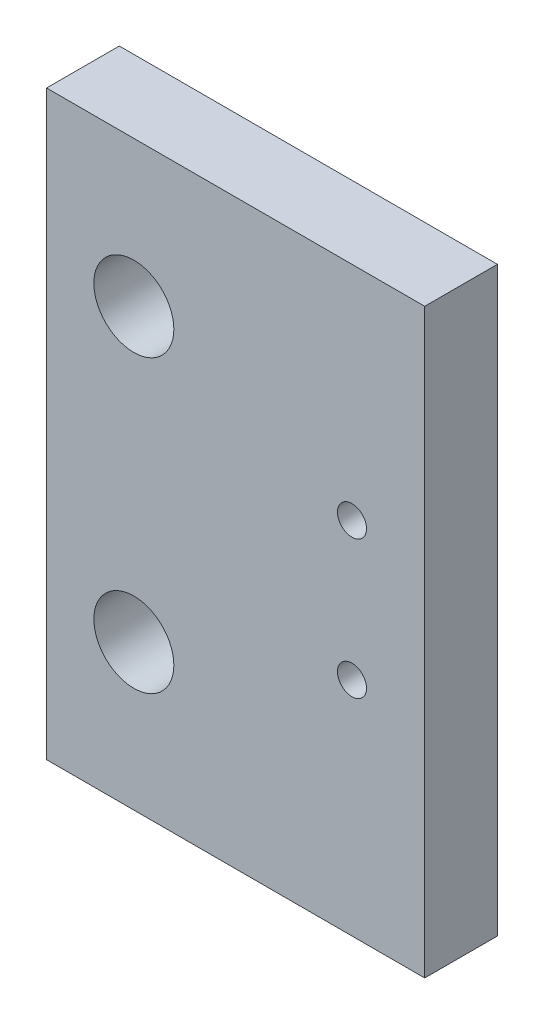
SolidWorks part; units mm, degrees
ref_plane "Plan de face" through (0, 0, 0) normal (0, 0, 1) x (1, 0, 0)
ref_plane "Plan de dessus" through (0, 0, 0) normal (0, 1, 0) x (1, 0, 0)
ref_plane "Plan de droite" through (0, 0, 0) normal (1, 0, 0) x (0, 0, -1)
sketch "Esquisse1" plane through (0, 0, 0) normal (0, 0, 1) x (1, 0, 0)
  line L0 (-38.6032, 13.3792) -> (-38.6032, -6.6208) construction
  line L1 (-44.6032, 23.3792) -> (-18.6032, 23.3792)
  line L2 (-44.6032, 23.3792) -> (-44.6032, -16.6208)
  line L3 (-44.6032, -16.6208) -> (-18.6032, -16.6208)
  line L4 (-18.6032, 23.3792) -> (-18.6032, -16.6208)
  line L5 (-23.6032, 8.1292) -> (-23.6032, -1.3708) construction
  circle A0 centre (-38.6032, 13.3792) radius 2.75
  circle A1 centre (-38.6032, -6.6208) radius 2.75
  circle A2 centre (-23.6032, 8.1292) radius 1
  circle A3 centre (-23.6032, -1.3708) radius 1
  point P8 (-38.6032, 3.3792)
  point P10 (-44.6032, 3.3792)
  point P15 (-23.6032, 3.3792)
  point P16 (-18.6032, 3.3792)
  dimension "D3" = 5.5
  dimension "D6" = 2
  dimension "D1" = 20
  dimension "D2" = 40
  dimension "D4" = 6
  dimension "D5" = 5
  dimension "D7" = 15
  dimension "D8" = 9.5
extrude "Boss.-Extru.1" add sketch "Esquisse1" along normal blind 5
